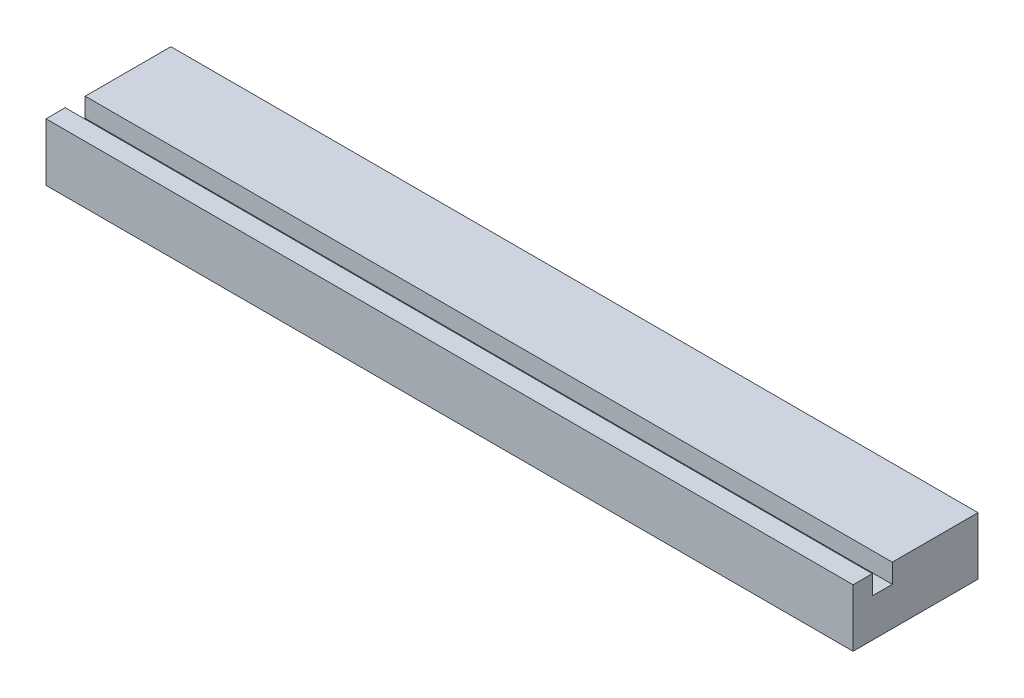
SolidWorks part; units mm, degrees
material "Pine"
ref_plane "Front Plane" through (0, 0, 0) normal (0, 0, 1) x (1, 0, 0)
ref_plane "Top Plane" through (0, 0, 0) normal (0, 1, 0) x (1, 0, 0)
ref_plane "Right Plane" through (0, 0, 0) normal (1, 0, 0) x (0, 0, -1)
sketch "Sketch1" plane through (0, 0, 0) normal (0, 0, 1) x (1, 0, 0)
  line L1 (-133.35, -9.525) -> (133.35, -9.525)
  line L2 (-133.35, -9.525) -> (-133.35, 9.525)
  line L3 (-133.35, 9.525) -> (133.35, 9.525)
  line L4 (133.35, -9.525) -> (133.35, 9.525)
  line L5 (-133.35, -9.525) -> (133.35, 9.525) construction
  line L6 (-133.35, 9.525) -> (133.35, -9.525) construction
  point P0 (0, 0)
  dimension "D1" = 19.05
  dimension "D2" = 266.7
extrude "Boss-Extrude1" add sketch "Sketch1" along normal blind 41.275
sketch "Sketch2" plane through (0, 9.525, 0) normal (0, 1, 0) x (1, 0, 0)
  line L0 (-133.35, -41.275) -> (-133.35, 0) construction
  line L1 (-133.35, -34.925) -> (133.35, -34.925)
  line L2 (-133.35, -34.925) -> (-133.35, -28.321)
  line L3 (-133.35, -28.321) -> (133.35, -28.321)
  line L4 (133.35, -34.925) -> (133.35, -28.321)
  line L5 (133.35, -41.275) -> (133.35, 0) construction
  line L6 (133.35, -41.275) -> (-133.35, -41.275) construction
  dimension "D1" = 6.35
  dimension "D2" = 6.604
extrude "Cut-Extrude1" cut sketch "Sketch2" against normal blind 6.35
